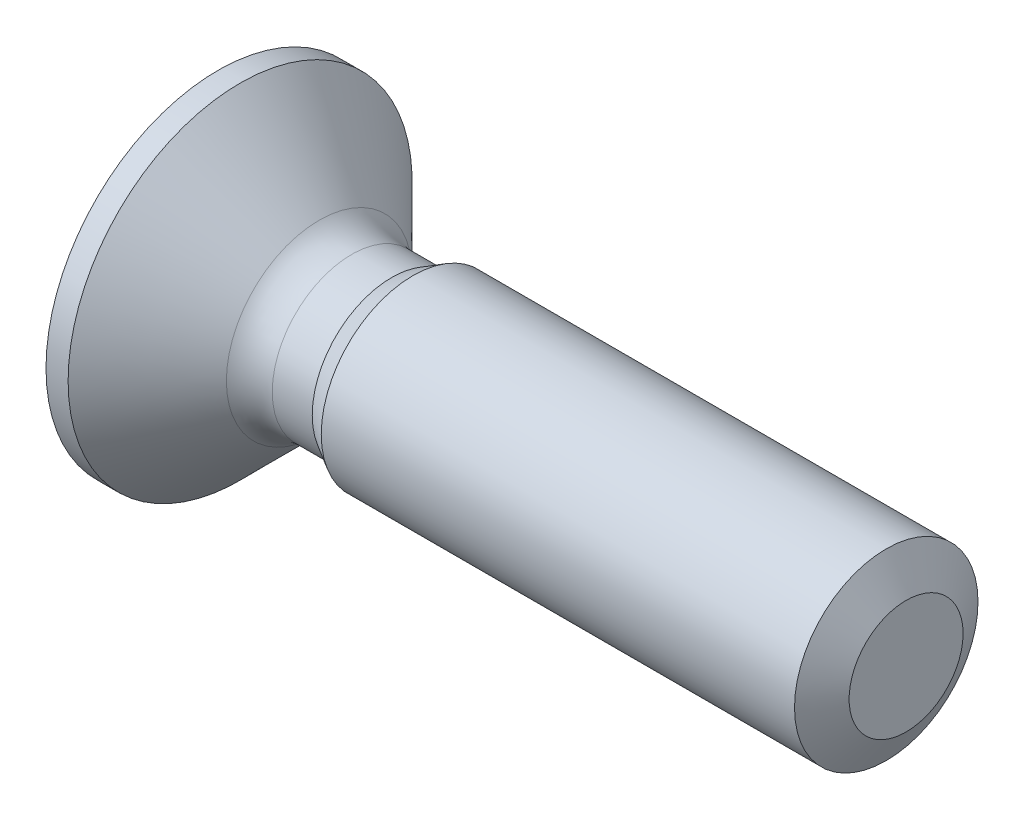
SolidWorks part; units mm, degrees
revolve "基体-旋转" add sketch "草图1" angle 360 about L0
sketch "草图1" plane through (0, 0, 0) normal (0, 0, 1) x (1, 0, 0)
  line L0 (0, 0) -> (4.4175, 0) construction
  line L1 (0, 0) -> (0, 1.5)
  line L2 (0, 1.5) -> (0.1928, 1.5)
  line L3 (0.1928, 1.5) -> (0.8828, 0.81)
  line L4 (1.1657, 0.6928) -> (1.5143, 0.6928)
  line L5 (1.5143, 0.6928) -> (1.7, 0.8)
  line L6 (1.7, 0.8) -> (6, 0.8)
  line L7 (6, 0.8) -> (6, 0)
  line L8 (0, 0) -> (6, 0)
  arc A0 (1.1657, 0.6928) -> (0.8828, 0.81) centre (1.1657, 1.0928) cw
  point P12 (1, 0.6928)
  dimension "D2" = 0.4
  dimension "D1" = 1.3856
  dimension "d" = 1.6
  dimension "dk" = 3
  dimension "k" = 1
  dimension "D5" = 45
  dimension "a" = 0.7
  dimension "l" = 6
  dimension "D8" = 30
cosmetic thread "装饰螺纹线2" parameters "D1"=4.3, "D2"=1.25
material "AISI 304"
ref_plane "前视" through (0, 0, 0) normal (0, 0, 1) x (1, 0, 0)
ref_plane "上视" through (0, 0, 0) normal (0, 1, 0) x (1, 0, 0)
ref_plane "右视" through (0, 0, 0) normal (1, 0, 0) x (0, 0, -1)
sketch "尺寸草图" plane through (0, 0, 0) normal (0, 0, 1) x (1, 0, 0)
  line L0 (0, 0) -> (6, 0)
  point P3 (1, 0)
  point P4 (0.7, 0)
  point P5 (1.6, 0)
  point P6 (3, 0)
  point P7 (4.4, 0)
  point P8 (3.5943, 0)
  point P9 (5.6, 0)
  point P10 (5.1, 0)
  point P11 (5.65, 0)
  dimension "d" = 1.6
  dimension "dk" = 3
  dimension "k" = 1
  dimension "a" = 0.7
  dimension "l" = 6
  dimension "r" = 0.4
  dimension "m" = 1.6
  dimension "h" = 0.9
  dimension "p" = 0.35
sketch "草图2" plane through (0, 0, 0) normal (0, 0, 1) x (1, 0, 0)
  line L0 (5.8269, 0.8) -> (6.1769, 0.8)
  line L1 (6.1769, 0.8) -> (6, 0.4969)
  line L2 (6, 0.4969) -> (5.8269, 0.8)
  line L3 (6, -0.8) -> (6, 0.8) construction
  line L6 (0, 0) -> (-0.4315, 0) construction
  dimension "D1" = 0.35
  dimension "D2" = 0.3031
  dimension "D3" = 0.8
  dimension "D4" = 60
revolve "切除-旋转1" cut sketch "草图2" angle 360 about L6
pattern_linear "阵列(线性)1" [suppressed] count 12 spacing 0.35 along (1, 0, 0)
sketch "草图3" plane through (0, 0, 0) normal (-1, 0, 0) x (0, 0, 1)
  line L0 (0, 0) -> (1.6329, 0) construction
  line L1 (0, 0) -> (0, 0.8499) construction
  line L2 (-0.8, 0.175) -> (0.8, 0.175)
  line L3 (-0.8, 0.175) -> (-0.8, -0.175)
  line L4 (-0.8, -0.175) -> (0.8, -0.175)
  line L5 (0.8, 0.175) -> (0.8, -0.175)
  dimension "m" = 1.6
  dimension "D1" = 0.35
ref_plane "基准面1" through (0.9, 0, 0) normal (-1, 0, 0) x (0, 0, 1)
sketch "草图4" plane through (0.9, 0, 0) normal (-1, 0, 0) x (0, 0, 1)
  point P0 (0, 0)
loft "切除-放样1" cut profiles "草图3", "草图4"
pattern_circular "阵列(圆周)1" count 2 every 90 about axis through (0, 0, 0) along (1, 0, 0) of "切除-放样1"
equation "\"l@草图1\" = \"l@尺寸草图\""
equation "\"k@草图1\" = \"k@尺寸草图\""
equation "\"a@草图1\" = \"a@尺寸草图\""
equation "\"d@草图1\" = \"d@尺寸草图\""
equation "\"dk@草图1\" = \"dk@尺寸草图\""
equation "\"D2@草图1\" = \"r@尺寸草图\""
equation "\"m@草图3\" = \"m@尺寸草图\""
equation "\"h@基准面1\" = \"h@尺寸草图\""
equation "\"D3@阵列(线性)1\" = \"p@尺寸草图\""
equation "\"D3@草图2\" = \"d@草图1\" / 2"
equation "\"D1@装饰螺纹线2\" = \"l@草图1\" - \"k@草图1\" - \"a@草图1\""
equation "\"D2@装饰螺纹线2\" = \"d@尺寸草图\"- \"p@尺寸草图\""
equation "\"D1@阵列(线性)1\" = (  \"l@草图1\" - \"k@草图1\" - \"a@草图1\" )  / \"p@尺寸草图\""
equation "\"D1@草图3\" = \"p@尺寸草图\""
equation "\"D1@草图1\" = \"d@尺寸草图\"*0.866"
equation "\"D2@草图2\" = \"p@尺寸草图\"*0.866"
equation "\"D1@草图2\" = \"p@尺寸草图\""
